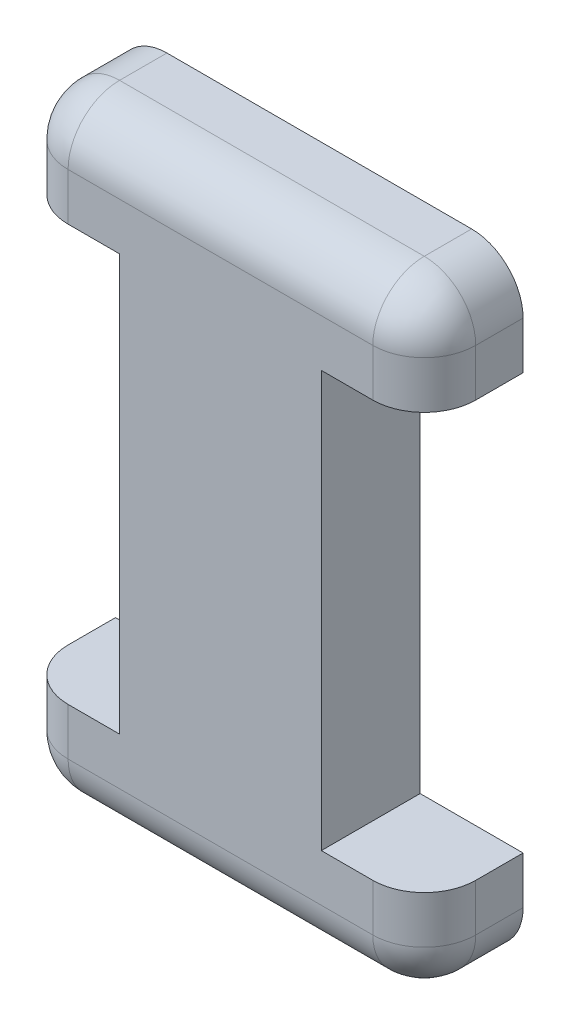
SolidWorks part; units mm, degrees
ref_plane "Front Plane" through (0, 0, 0) normal (1, 0, 0) x (0, 1, 0)
ref_plane "Top Plane" through (0, 0, 0) normal (0, 0, 1) x (0, 1, 0)
ref_plane "Right Plane" through (0, 0, 0) normal (0, 1, 0) x (-1, 0, 0)
sketch "Sketch1" plane through (0, 0, 0) normal (0, 0, 1) x (0, 1, 0)
  line L0 (-15, -4.9) -> (-15, -9.9)
  line L1 (-15, -4.9) -> (5.2, -4.9)
  line L3 (-15, 4.9) -> (5.2, 4.9)
  line L7 (-15, -9.9) -> (-19.8, -9.9)
  line L8 (-19.8, -9.9) -> (-19.8, 9.9)
  line L9 (-19.8, 9.9) -> (-15, 9.9)
  line L10 (-15, 9.9) -> (-15, 4.9)
  line L15 (5.2, 9.9) -> (5.2, 4.9)
  line L16 (10, 9.9) -> (5.2, 9.9)
  line L17 (10, -9.9) -> (10, 9.9)
  line L18 (5.2, -9.9) -> (10, -9.9)
  line L19 (5.2, -4.9) -> (5.2, -9.9)
  point P0 (0, 0)
  dimension "D1" = 4.8
  dimension "D2" = 9.8
  dimension "D3" = 19.8
  dimension "D4" = 5
  dimension "D5" = 4.8
  dimension "D6" = 4.8
  dimension "D7" = 20.2
  dimension "D8" = 20.2
  dimension "D9" = 4.8
  dimension "D10" = 19.8
  dimension "D11" = 9.8
extrude "Boss-Extrude1" add sketch "Sketch1" along normal blind 4.8 contours L1 L19 L18 L17 L16 L15 L3 L10 L9 L8 L7 L0
fillet "Fillet1" radius 2.5 10 edges at (-9.9, 10, 2.4) (-9.9, -19.8, 2.4) (9.9, 10, 2.4) (9.9, -19.8, 2.4) (9.9, -17.4, 4.8) (-9.9, -17.4, 4.8) (-9.9, 7.6, 4.8) (9.9, 7.6, 4.8) (0, 10, 4.8) (0, -19.8, 4.8)
